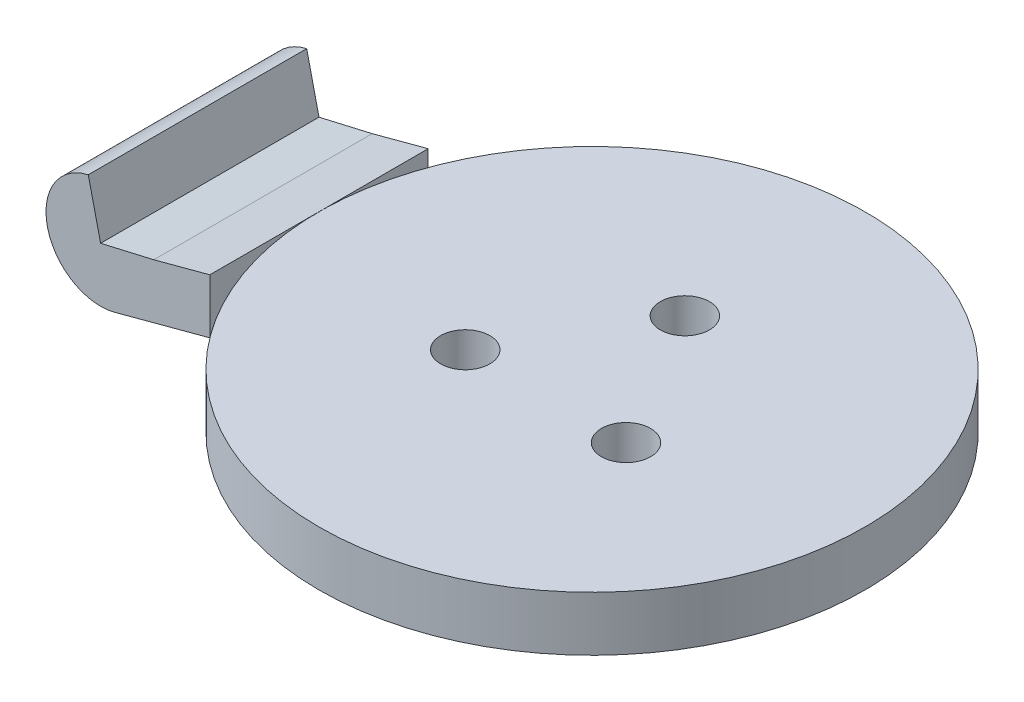
SolidWorks part; units mm, degrees
ref_plane "Спереди" through (0, 0, 0) normal (0, 0, 1) x (1, 0, 0)
ref_plane "Сверху" through (0, 0, 0) normal (0, 1, 0) x (1, 0, 0)
ref_plane "Справа" through (0, 0, 0) normal (1, 0, 0) x (0, 0, -1)
sketch "Эскиз1" plane through (0, 0, 0) normal (0, 1, 0) x (1, 0, 0)
  circle A0 centre (0, 0) radius 25
  circle A1 centre (0, 0) radius 8.5 construction
  circle A2 centre (0, 8.5) radius 2.25
  circle A3 centre (7.3612, -4.25) radius 2.25
  circle A4 centre (-7.3612, -4.25) radius 2.25
  point P8 (0, 0)
  point P9 (0, 0)
  dimension "D1" = 50
  dimension "D2" = 17
  dimension "D3" = 4.5
  dimension "D4" = 3
extrude "Бобышка-Вытянуть1" add sketch "Эскиз1" along normal mid plane 5
sketch "Эскиз4" plane through (0, 0, 0) normal (0, 0, 1) x (1, 0, 0)
  circle A0 centre (-35, 0) radius 5
  point P2 (0, 0)
  dimension "D1" = 10
  dimension "D2" = 35
extrude "Бобышка-Вытянуть2" add sketch "Эскиз4" along normal mid plane 20 separate body
sketch "Эскиз5" plane through (0, 0, -10) normal (0, 0, -1) x (-1, 0, 0)
  line L0 (25, 2.5) -> (25, -2.5)
  line L1 (25, -2.5) -> (33.7075, -4.8301)
  line L2 (33.7075, -4.8301) -> (33.7075, 0.1699)
  line L3 (33.7075, 0.1699) -> (25, 2.5)
  circle A1 centre (35, 0) radius 5 construction
  circle A2 centre (35, 0) radius 5 construction
  point P9 (0, 0)
extrude "Бобышка-Вытянуть3" add sketch "Эскиз5" against normal up to surface (20 mm away) up to face at (-30, 0, 10)
sketch "Эскиз6" plane through (0, 0, -10) normal (0, 0, -1) x (-1, 0, 0)
  line L0 (30.1288, 1.1276) -> (35, 0)
  line L1 (30.1288, 1.1276) -> (25, 2.5) construction
  line L2 (35, 0) -> (36.1276, 4.8712)
  arc A0 (33.7075, -4.8301) -> (30.1288, 1.1276) centre (35, 0) ccw construction
  circle A1 centre (35, 0) radius 5
  point P8 (0, 0)
  point P9 (30.1288, 1.1276)
  arc M4 (33.7075, -4.8301) -> (30.1288, 1.1276) centre (35, 0) ccw
  dimension "D1" = 90
extrude "Вырез-Вытянуть1" cut sketch "Эскиз6" against normal through all contours L0 L2 M4
equation "\"motor_diameter\"= 30"
equation "\"mm_diameter\"= IIF ( \"motor_diameter\" < 34 , 41 , \"motor_diameter\" + 8 )"
equation "\"upper_shafts_diameter\"= 5"
equation "\"upper_shats_length\"= 180"
equation "\"upper_bearing_d1\"= 10"
equation "\"upper_bearing_d2\"= 5"
equation "\"upper_bearing_h\"= 15"
equation "\"lower_shafts_diameter\"= 5"
equation "\"lower_shafts_length\"= 180"
equation "\"lower_bearing_d1\"= 10"
equation "\"lower_bearing_d2\"= 5"
equation "\"lower_bearing_h\"= 15"
equation "\"print_offset\"= 0.5"
equation "\"bh_screws_d\"= 2"
equation "\"bh_screws_h\"= 20"
equation "\"bh_screws_hh_d\"= 3.4"
equation "\"bh_screws_hh_h\"= 2"
equation "\"bh_nut_d\"= 3.8"
equation "\"bh_nut_h\"= 2"
equation "\"motor_screws_d\"= 3"
equation "\"motor_screws_h\"= 16"
equation "\"motor_screws_hh_d\"= 5.5"
equation "\"motor_screws_hh_h\"= 3"
equation "\"plate_hole_distance\"= 25.4"
equation "\"plate_screws_d\"= 6.5"
equation "\"shafts_diameter\"= IIF ( \"mm_diameter\" < 42 , 42 + 8 , \"mm_diameter\" + 8 )"
equation "\"central_hole_diameter\"= 8"
equation "\"bh_thikness\"= 4"
equation "\"ends_screws_d\"= 4"
equation "\"ends_screws_h\"= 16"
equation "\"ends_screws_hh_d\"= 6.7"
equation "\"ends_screws_hh_h\"= 4.1"
equation "\"ends_nut_d\"= 6.8"
equation "\"ends_nut_h\"= 3"
equation "\"system_radius\" = ( \"shafts_diameter\" + 12 + \"bh_thikness\" / 2 ) / 2"
equation "\"encoder_distance\"= \"system_radius\" + 4"
equation "\"tape_position\"= \"encoder_distance\" - 2 + 3.9 + 1.7 / 2"
equation "\"radial_bearing_d1\"= 7.7"
equation "\"radial_bearing_d2\"= 16"
equation "\"radial_bearing_h\"= 5"
equation "\"bearing_distance\"= \"encoder_distance\" + 2"
equation "\"platform_l\"= 70"
equation "\"D1@Эскиз1\"=\"shafts_diameter\""
equation "\"D3@Эскиз1\"=\"ends_screws_d\"+\"print_offset\""
equation "\"platform_thikness\"= 5"
equation "\"D1@Бобышка-Вытянуть1\"=\"platform_thikness\""
equation "\"sh_a\"= 20"
equation "\"sh_b\" = 10"
equation "\"D1@Эскиз4\"=\"sh_b\""
equation "\"D2@Эскиз4\"=\"platform_l\"/2"
equation "\"D1@Бобышка-Вытянуть2\"=\"sh_a\""
